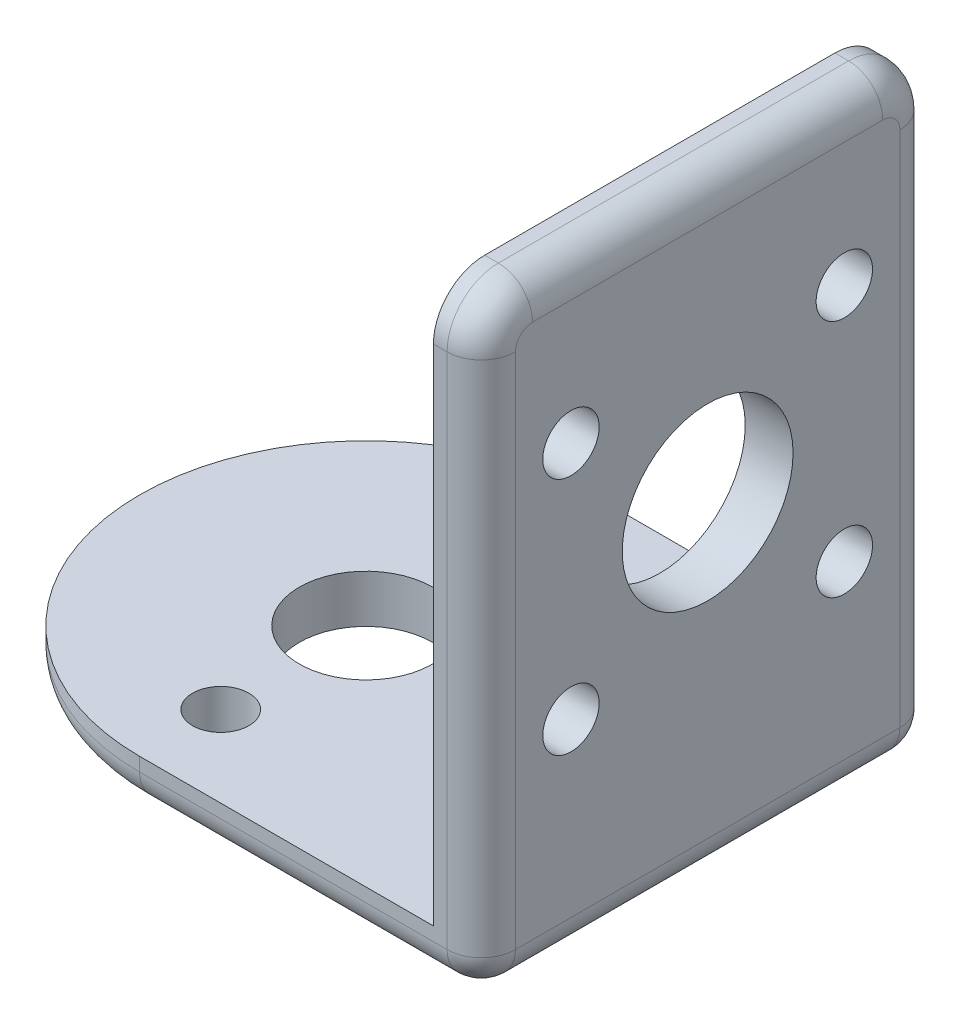
SolidWorks part; units mm, degrees
ref_plane "前视基准面" through (0, 0, 0) normal (0, 0, 1) x (1, 0, 0)
ref_plane "上视基准面" through (0, 0, 0) normal (0, 1, 0) x (1, 0, 0)
ref_plane "右视基准面" through (0, 0, 0) normal (1, 0, 0) x (0, 0, -1)
sketch "草图1" plane through (0, 0, 0) normal (1, 0, 0) x (0, 0, -1)
  line L0 (13.25, 2.4554) -> (13.25, -40.7384) construction
  line L1 (0, 0) -> (26.5, 0)
  line L2 (0, 0) -> (0, -32.5)
  line L3 (0, -32.5) -> (26.5, -32.5)
  line L4 (26.5, 0) -> (26.5, -32.5)
  line L5 (-7.4292, -16.25) -> (36.6073, -16.25) construction
  circle A0 centre (13.25, -16.25) radius 5
  circle A1 centre (5.25, -9.25) radius 1.65
  circle A2 centre (21.25, -9.25) radius 1.65
  circle A3 centre (5.25, -23.25) radius 1.65
  circle A4 centre (21.25, -23.25) radius 1.65
  dimension "D3" = 10
  dimension "D4" = 3.3
  dimension "D5" = 3.3
  dimension "D6" = 3.3
  dimension "D7" = 3.3
  dimension "D1" = 26.5
  dimension "D2" = 32.5
  dimension "D8" = 16
  dimension "D9" = 14
  dimension "D10" = 14
  dimension "D11" = 7
  dimension "D12" = 8
  dimension "D13" = 8
  dimension "D14" = 7
extrude "凸台-拉伸1" add sketch "草图1" along normal blind 2.8
sketch "草图3" plane through (0, -32.5, 0) normal (0, -1, 0) x (1, 0, 0)
  line L0 (-33.5561, -13.25) -> (10.0426, -13.25) construction
  line L1 (2.8, 0) -> (-17.2, 0)
  line L2 (2.8, 0) -> (2.8, -26.5)
  line L3 (2.8, -26.5) -> (-17.2, -26.5)
  arc A0 (-17.2, 0) -> (-17.2, -26.5) centre (-17.2, -13.25) ccw
  circle A1 centre (-17.2, -13.25) radius 3.9
  circle A2 centre (-17.2, -4.75) radius 1.65
  circle A3 centre (-17.2, -21.75) radius 1.65
  dimension "D2" = 7.8
  dimension "D3" = 3.3
  dimension "D1" = 20
  dimension "D4" = 8.5
extrude "凸台-拉伸2" add sketch "草图3" along normal blind 2.8
fillet "圆角2" radius 3 1 edges at (1.4, 0, -26.5)
fillet "圆角3" radius 3 1 edges at (1.4, 0, 0)
fillet "圆角4" radius 2 1 edges at (2.8, -35.3, -13.25)
fillet "圆角5" radius 2 10 edges at (2.8, -0.8787, -25.6213) (2.2142, -34.7142, -26.5) (-8.2, -35.3, -26.5) (-30.45, -35.3, -13.25) (-8.2, -35.3, 0) (2.2142, -34.7142, 0) (2.8, -0.8787, -0.8787) (2.8, -18.15, -26.5) (2.8, -18.15, 0) (2.8, 0, -13.25)
